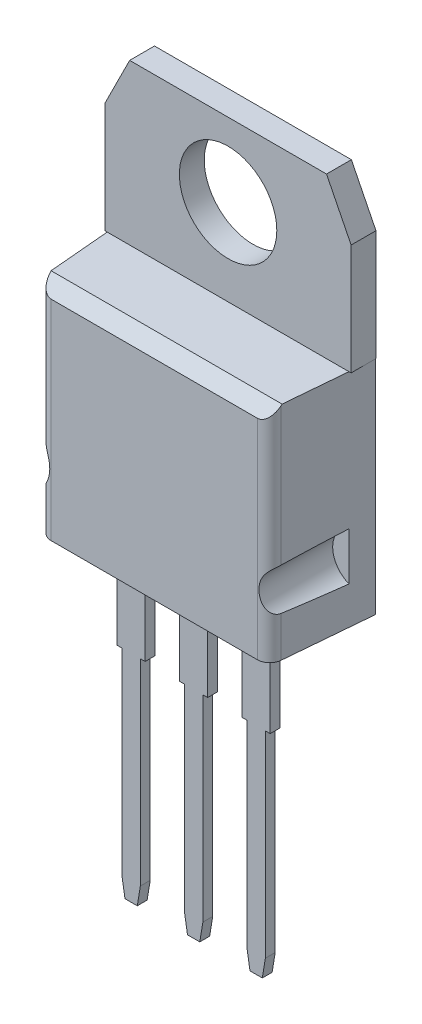
SolidWorks part; units mm, degrees
ref_plane "Front Plane" through (0, 0, 0) normal (0, 0, 1) x (1, 0, 0)
ref_plane "Top Plane" through (0, 0, 0) normal (0, 1, 0) x (1, 0, 0)
ref_plane "Right Plane" through (0, 0, 0) normal (1, 0, 0) x (0, 0, -1)
sketch "Sketch2" plane through (0, 0, 0) normal (0, 0, 1) x (1, 0, 0)
  line L1 (-5, -4.5) -> (5, -4.5)
  line L2 (-5, -4.5) -> (-5, 4.5)
  line L3 (-5, 4.5) -> (5, 4.5)
  line L4 (5, -4.5) -> (5, 4.5)
  line L5 (-5, -4.5) -> (5, 4.5) construction
  line L6 (-5, 4.5) -> (5, -4.5) construction
  point P0 (0, 0)
  dimension "D1" = 10
  dimension "D2" = 9
extrude "Boss-Extrude1" add sketch "Sketch2" along normal blind 4
chamfer "Chamfer1" distance 0.5 angle 45 1 edges at (0, 4.5, 4)
sketch "Sketch6" plane through (0, 0, 4) normal (0, 0, 1) x (1, 0, 0)
  line L0 (5, -4.5) -> (5, 4) construction
  line L1 (-5, -4.5) -> (5, -4.5) construction
  line L2 (5, -1) -> (5, -3)
  arc A0 (5, -3) -> (5, -1) centre (5.2917, -2) cw
  point P7 (4.25, -2)
  dimension "D1" = 1.5
  dimension "D2" = 2
  dimension "D3" = 0.75
extrude "Cut-Extrude1" cut sketch "Sketch6" against normal blind 3 contours A0 L2
mirror "Mirror1" about plane through (0, 0, 0) normal (1, 0, 0) of "Cut-Extrude1"
ref_plane "Plane1" through (0, 0, 2) normal (0, 0, 1) x (1, 0, 0)
sketch "Sketch7" plane through (0, 0, 2) normal (0, 0, 1) x (1, 0, 0)
  line L0 (-0.57, -4.5) -> (-0.57, -8.44)
  line L1 (-5, -4.5) -> (5, -4.5) construction
  line L2 (-0.57, -8.44) -> (-0.375, -8.44)
  line L3 (-0.375, -8.44) -> (-0.375, -16.44)
  line L4 (-0.375, -16.44) -> (-0.25, -17.2)
  line L5 (-0.25, -17.2) -> (0.25, -17.2)
  line L6 (0.25, -17.2) -> (0.375, -16.44)
  line L7 (0.375, -16.44) -> (0.375, -8.44)
  line L8 (0.375, -8.44) -> (0.57, -8.44)
  line L9 (0.57, -8.44) -> (0.57, -4.5)
  line L10 (0.57, -4.5) -> (-0.57, -4.5)
  point P5 (0, -17.2)
  dimension "D1" = 3.94
  dimension "D2" = 8.76
  dimension "D3" = 1.14
  dimension "D4" = 0.75
  dimension "D5" = 8
  dimension "D6" = 0.5
  dimension "D7" = 0.57
extrude "Boss-Extrude2" add sketch "Sketch7" along normal blind 0.4 contours L0 L2 L3 L4 L5 L6 L7 L8 L9 L10
pattern_linear "LPattern1" count 2 spacing 2.54 along (-1, 0, 0) of "Boss-Extrude2"
pattern_linear "LPattern2" count 2 spacing 2.54 along (1, 0, 0) of "Boss-Extrude2"
draft "Draft2" type of draft neutral plane draft angle 5 faces to draft 2 face at (5, -0.4444, 2.3889) face at (-5, -0.4444, 2.3889) neutral plane through (0, 0, 0) neutral plane normal (0, 0, -1) reverse direction yes parameters "D1"=5
sketch "Sketch8" plane through (0, 0, 0) normal (0, 0, -1) x (-1, 0, 0)
  line L0 (-5, 9) -> (-4, 11)
  line L1 (-5, 4.5) -> (5, 4.5)
  line L2 (-5, 4.5) -> (-5, 9)
  line L3 (-4, 11) -> (4, 11)
  line L4 (5, 4.5) -> (5, 9)
  line L5 (4, 11) -> (5, 9)
  circle A0 centre (0, 8) radius 1.98
  point P1 (5, 11)
  point P2 (-5, 11)
  dimension "D7" = 3.96
  dimension "D1" = 6.5
  dimension "D2" = 10
  dimension "D3" = 2
  dimension "D4" = 1
  dimension "D5" = 1
  dimension "D6" = 2
  dimension "D8" = 3
extrude "Boss-Extrude3" add sketch "Sketch8" against normal blind 1 and the other way blind 0.01
fillet "Fillet1" radius 0.5 2 edges at (-4.65, 1.4103, 4) (4.65, 1.4103, 4)
scale "Scale1" scale about origin uniform scaling yes scale factor 0.6
